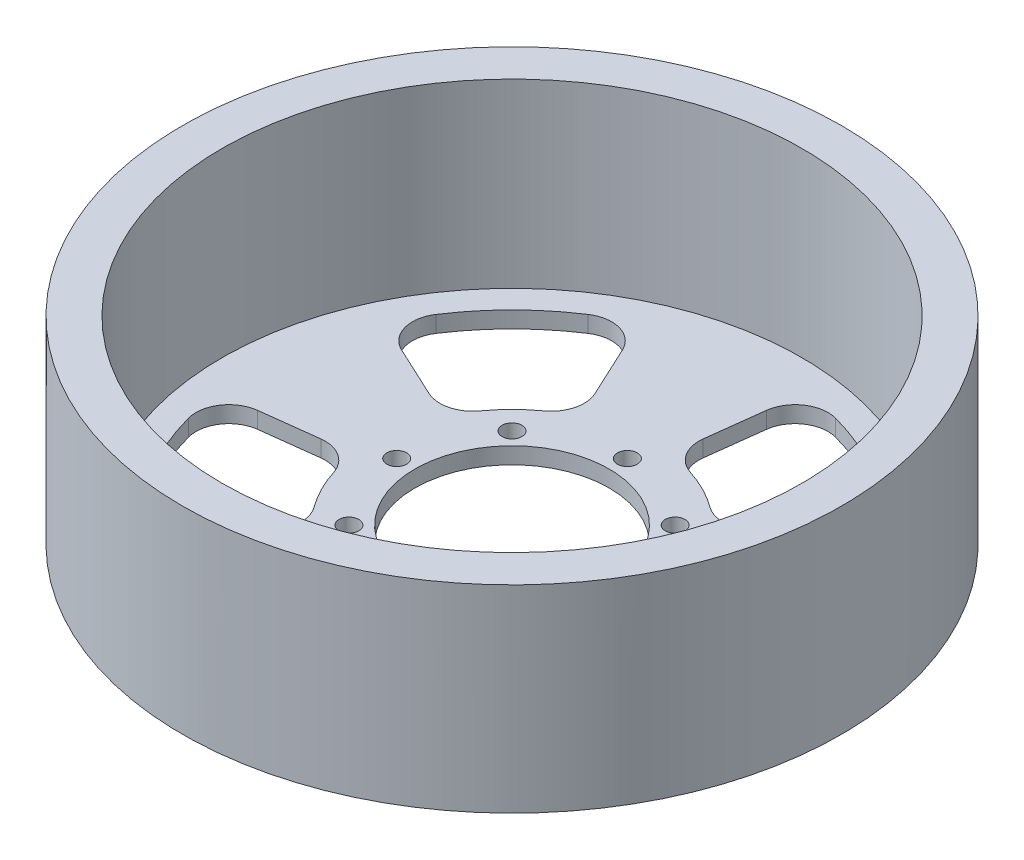
SolidWorks part; units mm, degrees
material "7050-T73510"
ref_plane "前视基准面" through (0, 0, 0) normal (0, 0, 1) x (1, 0, 0)
ref_plane "上视基准面" through (0, 0, 0) normal (0, 1, 0) x (1, 0, 0)
ref_plane "右视基准面" through (0, 0, 0) normal (1, 0, 0) x (0, 0, -1)
sketch "草图1" plane through (0, 0, 0) normal (0, 1, 0) x (1, 0, 0)
  circle A0 centre (0, 0) radius 50
  dimension "D1" = 100
extrude "凸台-拉伸1" add sketch "草图1" along normal blind 50
sketch "草图2" plane through (0, 50, 0) normal (0, 1, 0) x (1, 0, 0)
  circle A0 centre (0, 0) radius 44
  dimension "D1" = 88
extrude "切除-拉伸1" cut sketch "草图2" against normal blind 37.5
sketch "草图3" plane through (0, 0, 0) normal (0, -1, 0) x (1, 0, 0)
  circle A0 centre (0, 0) radius 44
  dimension "D1" = 88
extrude "切除-拉伸2" cut sketch "草图3" against normal blind 9.5
sketch "草图4" plane through (0, 12.5, 0) normal (0, 1, 0) x (1, 0, 0)
  circle A0 centre (0, 0) radius 14.75
  circle A1 centre (0, 0) radius 17.5 construction
  circle A2 centre (0, 17.5) radius 1.5
  circle A3 centre (12.3744, 12.3744) radius 1.5
  circle A4 centre (17.5, 0) radius 1.5
  circle A5 centre (12.3744, -12.3744) radius 1.5
  circle A6 centre (0, -17.5) radius 1.5
  circle A7 centre (-12.3744, -12.3744) radius 1.5
  circle A8 centre (-17.5, 0) radius 1.5
  circle A9 centre (-12.3744, 12.3744) radius 1.5
  point P22 (0, 0)
  dimension "D1" = 29.5
  dimension "D2" = 35
  dimension "D3" = 3
extrude "切除-拉伸3" cut sketch "草图4" against normal blind 4
sketch "草图5" plane through (0, 50, 0) normal (0, 1, 0) x (1, 0, 0)
  circle A0 centre (0, 0) radius 46.5
  dimension "D1" = 93
split line "分割线1"
sketch "草图7" plane through (0, 50, 0) normal (0, 1, 0) x (1, 0, 0)
  circle A0 centre (0, 0) radius 46.5
  dimension "D1" = 93
split line "分割线2"
sketch "草图8" plane through (0, 12.5, 0) normal (0, 1, 0) x (1, 0, 0)
  line L0 (0, 0) -> (18.1596, 35.6403) construction
  line L2 (0, 0) -> (0, 67.2498) construction
  line L10 (0, 0) -> (4.8748, 39.7018)
  line L11 (0, 0) -> (29.2541, 27.2799)
  circle A8 centre (0, 0) radius 21.5
  circle A9 centre (0, 0) radius 40
  dimension "D1" = 43
  dimension "D2" = 80
  dimension "D3" = 27
  dimension "D4" = 20
extrude "切除-拉伸4" cut sketch "草图8" against normal blind 4 contours L11 A9 L10 A8
fillet "圆角1" radius 5 4 edges at (29.2541, 11, -27.2799) (15.7241, 11, -14.663) (2.6202, 11, -21.3397) (4.8748, 11, -39.7018)
pattern_circular "阵列(圆周)1" count 5 over 360 about axis through (0, 0, 0) along (0, 1, 0) of "切除-拉伸4", "圆角1"
sketch "草图9" plane through (0, 0, 0) normal (0, -1, 0) x (1, 0, 0)
  circle A0 centre (0, 0) radius 46.5
  circle A1 centre (0, 0) radius 72.0126
  dimension "D1" = 93
sketch "草图11" plane through (0, 0, 0) normal (0, -1, 0) x (1, 0, 0)
  circle A0 centre (0, 0) radius 59.1651
extrude "切除-拉伸8" cut sketch "草图11" against normal blind 10
sketch "草图12" plane through (0, 10, 0) normal (0, -1, 0) x (1, 0, 0)
  circle A0 centre (0, 0) radius 46.5
  dimension "D1" = 93
split line "分割线3"
sketch "草图15" plane through (0, 50, 0) normal (0, 1, 0) x (1, 0, 0)
  circle A0 centre (0, 0) radius 58.0487
extrude "切除-拉伸10" cut sketch "草图15" against normal blind 10
